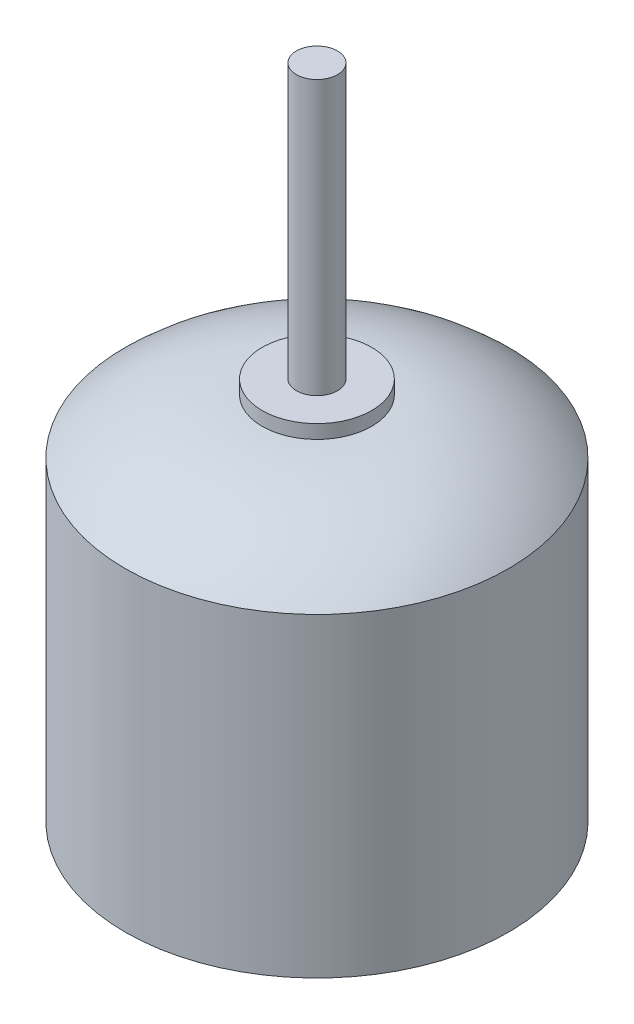
SolidWorks part; units mm, degrees
ref_plane "Front Plane" through (0, 0, 0) normal (0, 0, 1) x (1, 0, 0)
ref_plane "Top Plane" through (0, 0, 0) normal (0, 1, 0) x (1, 0, 0)
ref_plane "Right Plane" through (0, 0, 0) normal (1, 0, 0) x (0, 0, -1)
sketch "Sketch1" plane through (0, 0, 0) normal (0, 1, 0) x (1, 0, 0)
  circle A0 centre (0, 0) radius 14
  dimension "D1" = 28
extrude "Boss-Extrude1" add sketch "Sketch1" along normal blind 28
sketch "Sketch2" plane through (0, 0, 0) normal (0, -1, 0) x (1, 0, 0)
  line L0 (0, 14) -> (0, -14) construction
  line L1 (-14, 0) -> (14, 0) construction
  line L2 (0, -8) -> (0, 8) construction
  line L3 (-9.5, 0) -> (9.5, 0) construction
  circle A0 centre (0, 0) radius 14 construction
  circle A1 centre (0, 8) radius 1.5
  circle A2 centre (9.5, 0) radius 1.5
  circle A3 centre (0, -8) radius 1.5
  circle A4 centre (-9.5, 0) radius 1.5
  point P11 (0, 0)
  point P14 (0, 0)
  dimension "D3" = 3
  dimension "D1" = 19
  dimension "D2" = 16
extrude "Cut-Extrude1" cut sketch "Sketch2" against normal blind 4
sketch "Sketch4" plane through (0, 0, 0) normal (0, 0, 1) x (1, 0, 0)
  line L0 (-14, 23) -> (-14, 28)
  line L1 (-14, 28) -> (-14, 0) construction
  line L2 (-14, 28) -> (-4, 28)
  line L3 (14, 28) -> (-14, 28) construction
  line L4 (-4, 28) -> (-4, 27)
  arc A0 (-4, 27) -> (-14, 23) centre (-4, 12.5) ccw
  dimension "D1" = 10
  dimension "D2" = 5
  dimension "D3" = 1
ref_axis "Axis1" through (0, 28, 0) along (0, -1, 0)
revolve "Cut-Revolve1" cut sketch "Sketch4" angle 360 about axis through (0, 28, 0) along (0, -1, 0)
sketch "Sketch5" plane through (0, 28, 0) normal (0, 1, 0) x (1, 0, 0)
  circle A0 centre (0, 0) radius 1.5
  dimension "D1" = 3
extrude "Boss-Extrude2" add sketch "Sketch5" along normal blind 20
